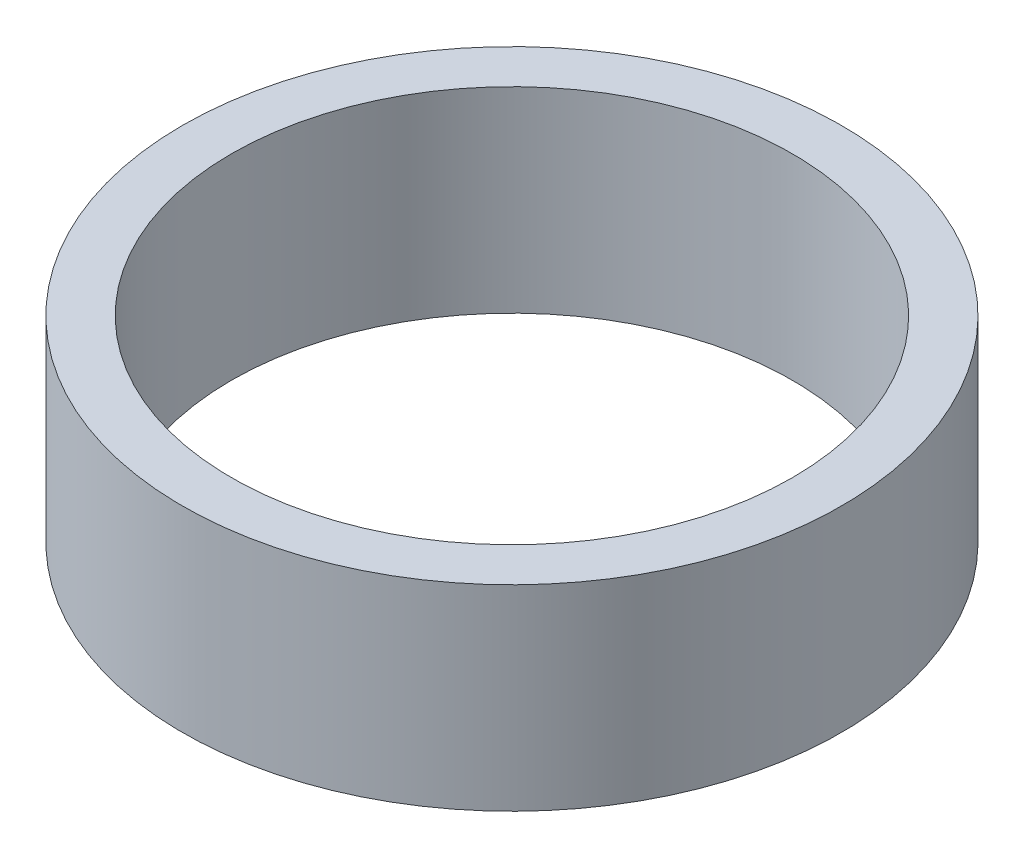
SolidWorks part; units mm, degrees
ref_plane "Front Plane" through (0, 0, 0) normal (0, 0, 1) x (1, 0, 0)
ref_plane "Top Plane" through (0, 0, 0) normal (0, 1, 0) x (1, 0, 0)
ref_plane "Right Plane" through (0, 0, 0) normal (1, 0, 0) x (0, 0, -1)
sketch "Sketch2" plane through (0, 0, 0) normal (0, 0, 1) x (1, 0, 0)
  line L0 (0, 25.4) -> (0, 0) construction
  line L1 (36.322, 0) -> (36.322, 25.4)
  line L2 (36.322, 25.4) -> (42.672, 25.4)
  line L3 (42.672, 25.4) -> (42.672, 0)
  line L4 (42.672, 0) -> (36.322, 0)
  dimension "D1" = 42.672
  dimension "D3" = 25.4
  dimension "D4" = 6.35
revolve "Revolve1" add sketch "Sketch2" angle 360 about L0
